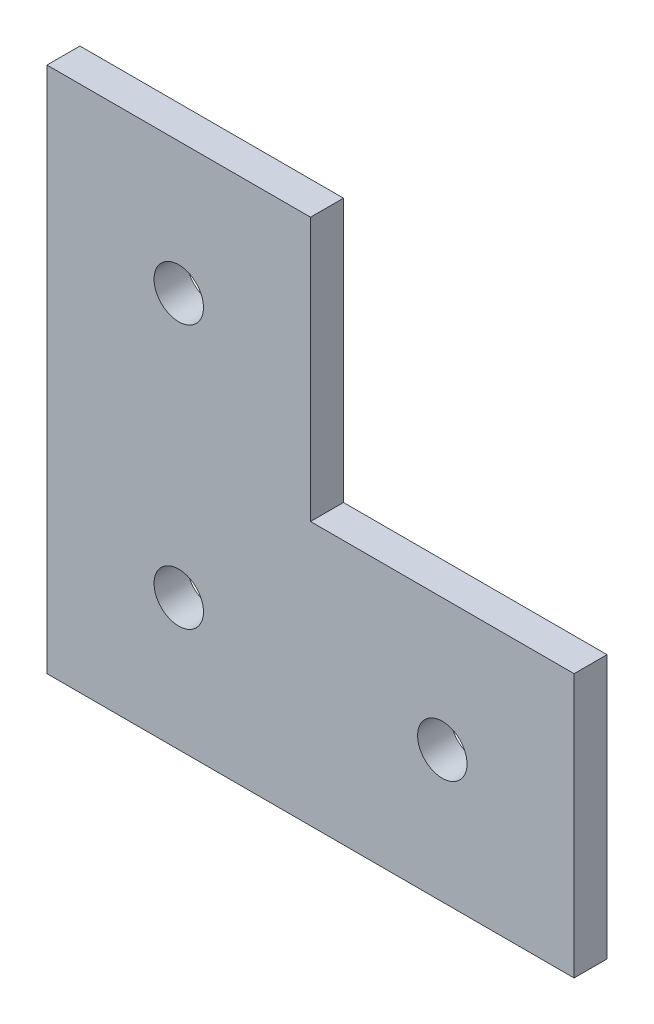
SolidWorks part; units mm, degrees
material "6063-T1"
ref_plane "Front Plane" through (0, 0, 0) normal (0, 0, 1) x (1, 0, 0)
ref_plane "Top Plane" through (0, 0, 0) normal (0, 1, 0) x (1, 0, 0)
ref_plane "Right Plane" through (0, 0, 0) normal (1, 0, 0) x (0, 0, -1)
sketch "Sketch1" plane through (0, 0, 0) normal (0, 0, 1) x (1, 0, 0)
  line L1 (0, 0) -> (50.8, 0)
  line L2 (0, 0) -> (0, 50.8)
  line L3 (0, 50.8) -> (50.8, 50.8)
  line L4 (50.8, 0) -> (50.8, 50.8)
  line L5 (50.8, 50.8) -> (25.4, 50.8)
  line L6 (50.8, 50.8) -> (50.8, 25.4)
  line L7 (50.8, 25.4) -> (25.4, 25.4)
  line L8 (25.4, 50.8) -> (25.4, 25.4)
  circle A0 centre (12.7, 12.7) radius 2.3813
  circle A1 centre (38.1, 12.7) radius 2.3813
  circle A2 centre (38.1, 38.1) radius 2.3813
  circle A3 centre (12.7, 38.1) radius 2.3813
  dimension "D5" = 4.7625
  dimension "D1" = 50.8
  dimension "D2" = 50.8
  dimension "D3" = 25.4
  dimension "D4" = 25.4
  dimension "D6" = 12.7
  dimension "D7" = 12.7
  dimension "D8" = 2
  dimension "D9" = 2
extrude "Boss-Extrude1" add sketch "Sketch1" along normal blind 3.175 contours L8 L3 L2 L1 L4 L7 A3 A1 A0
